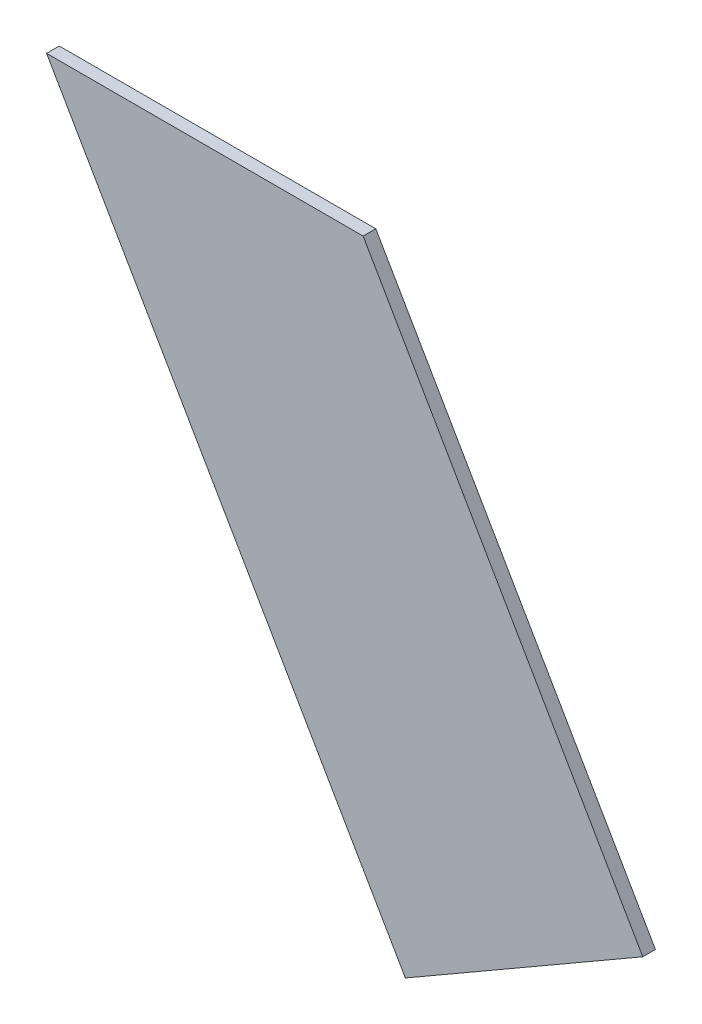
SolidWorks part; units mm, degrees
ref_plane "Front Plane" through (0, 0, 0) normal (0, 0, 1) x (1, 0, 0)
ref_plane "Top Plane" through (0, 0, 0) normal (0, 1, 0) x (1, 0, 0)
ref_plane "Right Plane" through (0, 0, 0) normal (1, 0, 0) x (0, 0, -1)
sketch "Sketch1" plane through (0, 0, 0) normal (0, 0, 1) x (1, 0, 0)
  line L0 (-66.6151, 32.8284) -> (8.3849, 32.8284)
  line L1 (-66.6151, 32.8284) -> (-17.3751, -52.4577)
  line L4 (-17.3751, -52.4577) -> (18.3849, -114.3959)
  line L5 (18.3849, -114.3959) -> (74.6349, -81.9199)
  line L6 (74.6349, -81.9199) -> (8.3849, 32.8284)
  dimension "D1" = 60
  dimension "D2" = 75
  dimension "D3" = 170
extrude "Boss-Extrude1" add sketch "Sketch1" along normal blind 3
